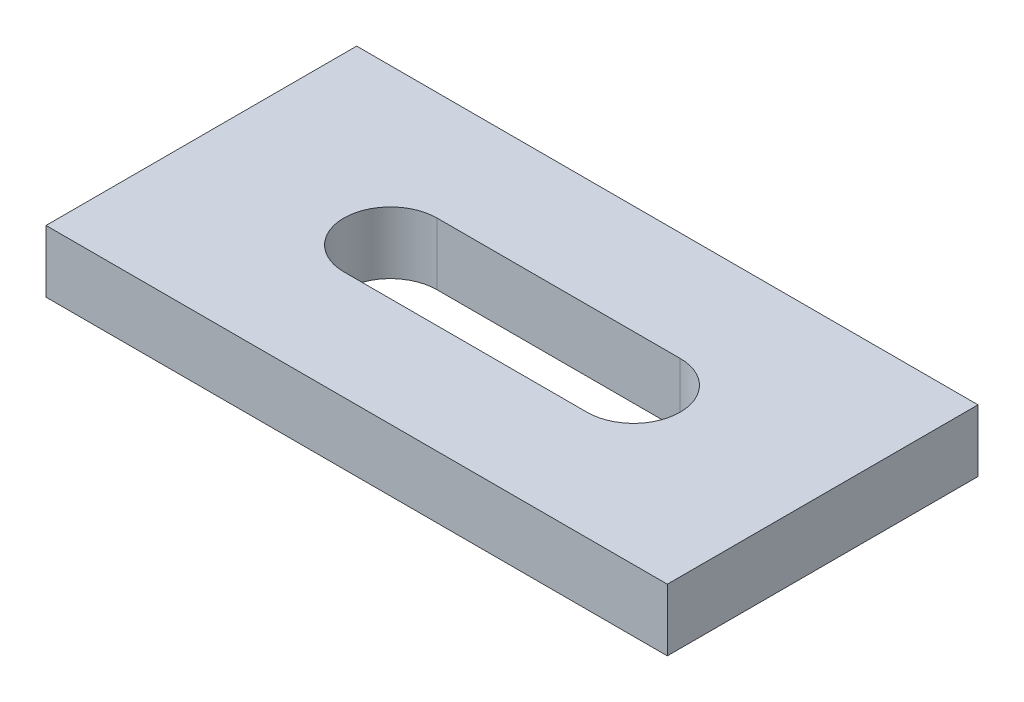
SolidWorks part; units mm, degrees
ref_plane "Front Plane" through (0, 0, 0) normal (0, 0, 1) x (1, 0, 0)
ref_plane "Top Plane" through (0, 0, 0) normal (0, 1, 0) x (1, 0, 0)
ref_plane "Right Plane" through (0, 0, 0) normal (1, 0, 0) x (0, 0, -1)
sketch "Sketch2" plane through (0, 0, 0) normal (0, 1, 0) x (1, 0, 0)
  line L0 (-39.1304, 0) -> (39.1304, 0) construction
  line L1 (-100, -50) -> (100, -50)
  line L2 (-100, -50) -> (-100, 50)
  line L3 (-100, 50) -> (100, 50)
  line L4 (100, -50) -> (100, 50)
  line L5 (-100, -50) -> (100, 50) construction
  line L6 (-100, 50) -> (100, -50) construction
  line L7 (-39.1304, 15) -> (39.1304, 15)
  line L8 (-39.1304, -15) -> (39.1304, -15)
  arc A0 (-39.1304, 15) -> (-39.1304, -15) centre (-39.1304, 0) ccw
  arc A1 (39.1304, -15) -> (39.1304, 15) centre (39.1304, 0) ccw
  point P0 (0, 0)
  point P8 (0, 0)
  dimension "D3" = 15
  dimension "D1" = 200
  dimension "D2" = 100
extrude "Boss-Extrude2" add sketch "Sketch2" along normal blind 20
